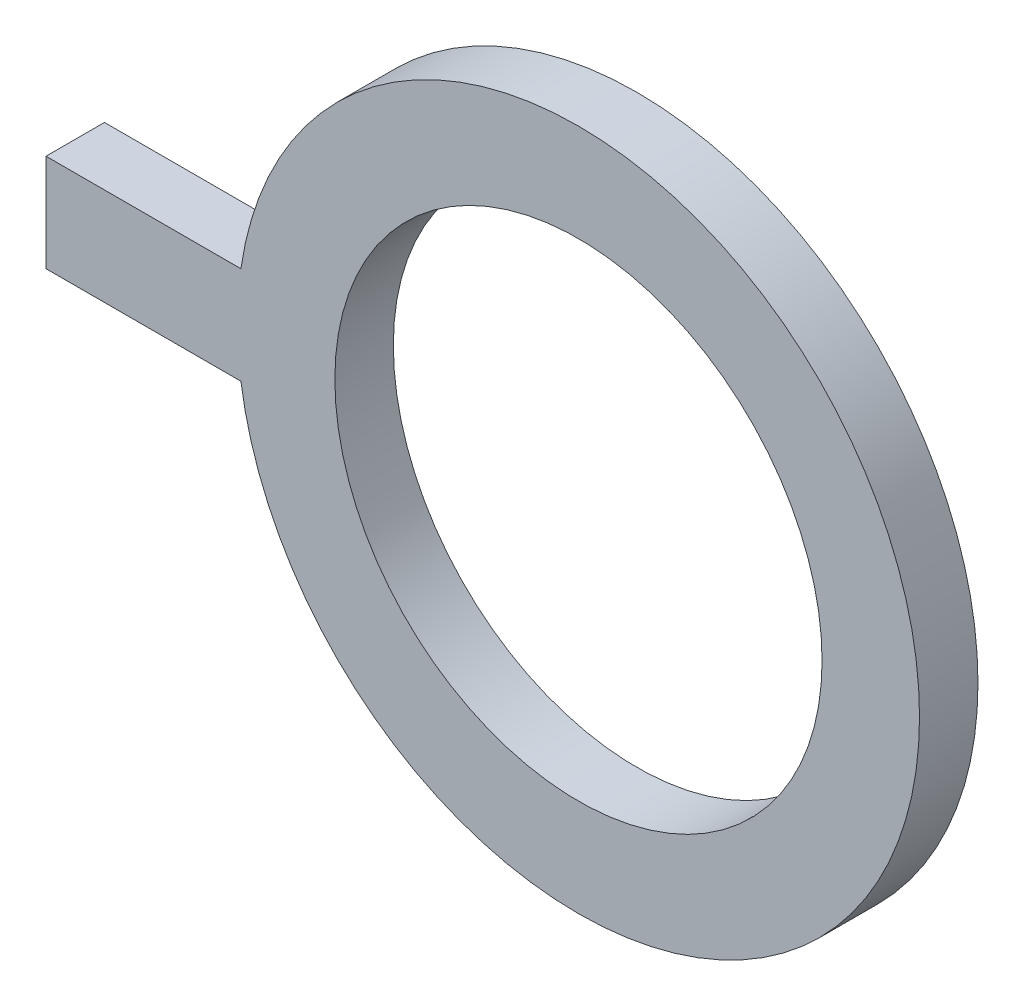
SolidWorks part; units mm, degrees
material "Balsa"
ref_plane "Front Plane" through (0, 0, 0) normal (1, 0, 0) x (0, 1, 0)
ref_plane "Top Plane" through (0, 0, 0) normal (0, 0, 1) x (0, 1, 0)
ref_plane "Right Plane" through (0, 0, 0) normal (0, 1, 0) x (-1, 0, 0)
sketch "Sketch1" plane through (0, 0, 0) normal (0, 0, 1) x (0, 1, 0)
  line L0 (0, 0) -> (0, 54.641) construction
  line L1 (5, 34.641) -> (5, 54.641)
  line L2 (-5, 34.641) -> (-5, 54.641)
  line L3 (-5, 54.641) -> (5, 54.641)
  circle A0 centre (0, 0) radius 25
  arc A1 (-5, 34.641) -> (5, 34.641) centre (0, 0) ccw
  circle A3 centre (0, 0) radius 35 construction
  point P4 (0, 0)
  point P10 (37.5, 0)
  dimension "D1" = 50
  dimension "D3" = 20
  dimension "D4" = 10
  dimension "D2" = 10
extrude "Boss-Extrude1" add sketch "Sketch1" along normal blind 6
